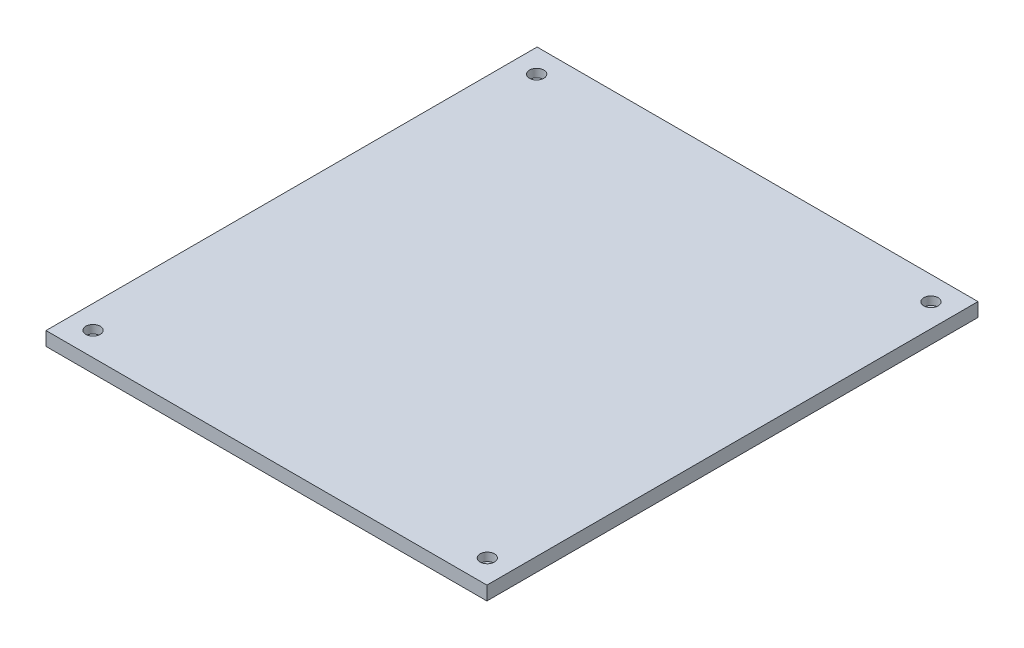
SolidWorks part; units mm, degrees
ref_plane "Front Plane" through (0, 0, 0) normal (0, 0, 1) x (1, 0, 0)
ref_plane "Top Plane" through (0, 0, 0) normal (0, 1, 0) x (1, 0, 0)
ref_plane "Right Plane" through (0, 0, 0) normal (1, 0, 0) x (0, 0, -1)
sketch "Sketch1" plane through (0, 0, 0) normal (0, 1, 0) x (1, 0, 0)
  line L0 (-75, 84.105) -> (-75, 83.5359)
  line L1 (-80, 89.105) -> (80, 89.105)
  line L2 (-80, 89.105) -> (-80, -89.105)
  line L3 (-80, -89.105) -> (80, -89.105)
  line L4 (80, 89.105) -> (80, -89.105)
  line L5 (-80, 89.105) -> (80, -89.105) construction
  line L6 (-80, -89.105) -> (80, 89.105) construction
  line L12 (-75, 84.105) -> (75, 84.105) construction
  line L14 (-75, 84.105) -> (-75, -84.105) construction
  line L17 (-75, -84.105) -> (75, -84.105) construction
  line L18 (75, 84.105) -> (75, -84.105) construction
  circle A1 centre (-71.5388, 80.4967) radius 1.5
  circle A3 centre (71.5388, 80.4967) radius 1.5
  circle A4 centre (71.5388, -80.4967) radius 1.5
  circle A7 centre (-71.5388, -80.4967) radius 1.5
  point P0 (0, 0)
  dimension "D5" = 3
  dimension "D1" = 160
  dimension "D2" = 178.21
  dimension "D3" = 5
extrude "Boss-Extrude2" add sketch "Sketch1" along normal blind 5
sketch "Sketch2" plane through (0, 5, 0) normal (0, 1, 0) x (1, 0, 0)
  circle A0 centre (-71.5388, 80.4967) radius 2.6
  circle A1 centre (71.5388, 80.4967) radius 2.6
  circle A2 centre (71.5388, -80.4967) radius 2.6
  circle A3 centre (-71.5388, -80.4967) radius 2.6
  dimension "D1" = 5.2
extrude "Cut-Extrude1" cut sketch "Sketch2" against normal blind 3
